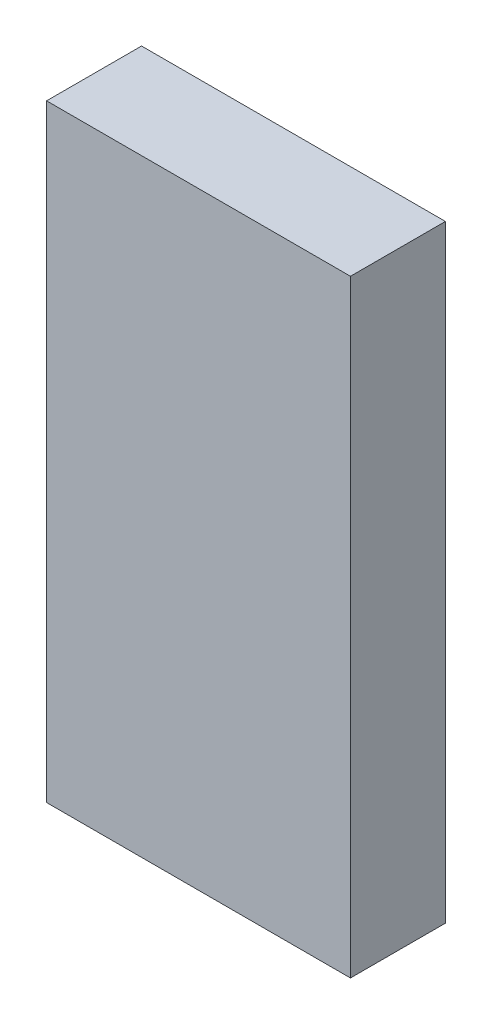
SolidWorks part; units mm, degrees
material "Low Carbon Steel"
ref_plane "Front Plane" through (0, 0, 0) normal (0, 0, 1) x (1, 0, 0)
ref_plane "Top Plane" through (0, 0, 0) normal (0, 1, 0) x (1, 0, 0)
ref_plane "Right Plane" through (0, 0, 0) normal (1, 0, 0) x (0, 0, -1)
sketch "Sketch1" plane through (0, 0, 0) normal (0, 0, 1) x (1, 0, 0)
  line L1 (0, 0) -> (101.6, 0)
  line L2 (0, 0) -> (0, 203.2)
  line L3 (0, 203.2) -> (101.6, 203.2)
  line L4 (101.6, 0) -> (101.6, 203.2)
  dimension "D1" = 101.6
  dimension "D2" = 203.2
extrude "Boss-Extrude1" add sketch "Sketch1" along normal blind 31.75
other "Freeze***"
